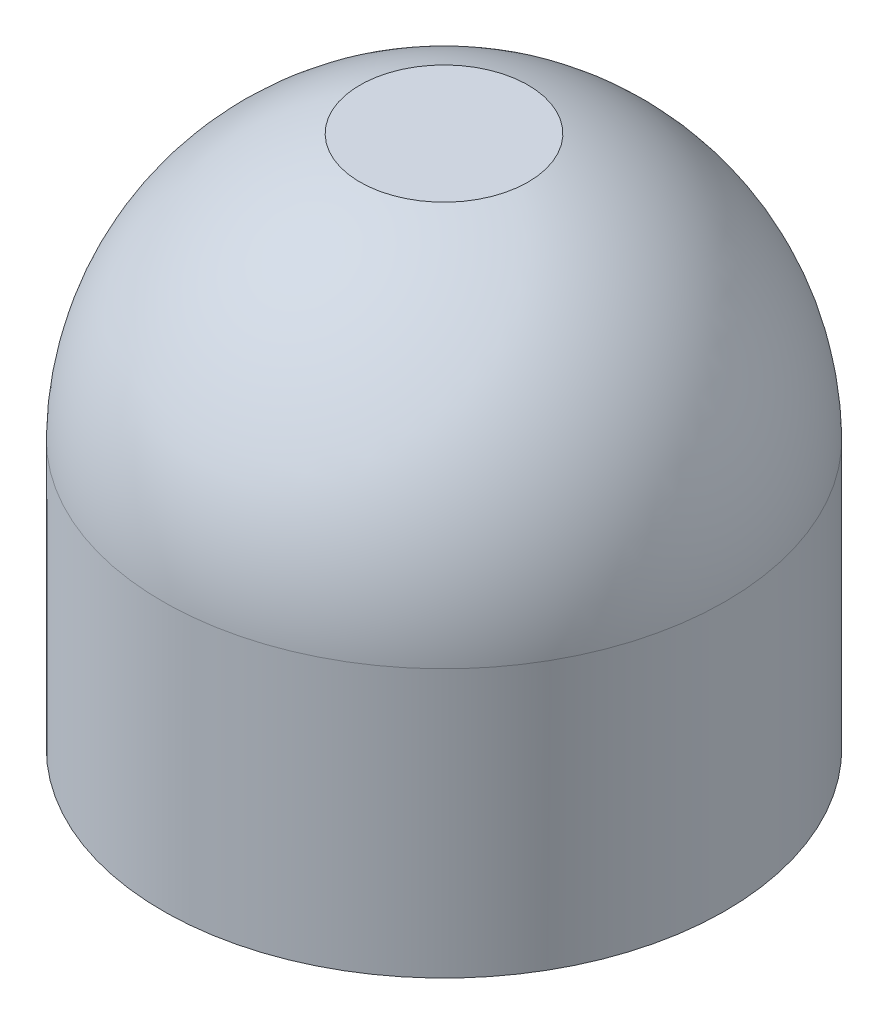
SolidWorks part; units mm, degrees
ref_plane "Front Plane" through (0, 0, 0) normal (0, 0, 1) x (1, 0, 0)
ref_plane "Top Plane" through (0, 0, 0) normal (0, 1, 0) x (1, 0, 0)
ref_plane "Right Plane" through (0, 0, 0) normal (1, 0, 0) x (0, 0, -1)
sketch "Sketch1" plane through (0, 0, 0) normal (0, 1, 0) x (1, 0, 0)
  circle A0 centre (0, 0) radius 5.25
  circle A1 centre (0, 0) radius 4.5
  point P5 (0, 0)
  dimension "D1" = 10.5
  dimension "D2" = 9
extrude "Boss-Extrude1" add sketch "Sketch1" along normal blind 5
sketch "Sketch2" plane through (0, 0, 0) normal (0, 1, 0) x (1, 0, 0)
  line L1 (1.3277, 3.7956) -> (1.3277, 5.7011)
  line L2 (1.3277, 5.7011) -> (-1.5, 5.7011)
  line L3 (-1.5, 5.7011) -> (-1.5, 3.7011)
  line L4 (-1.5, 3.7011) -> (1.3277, 3.7956)
extrude "Cut-Extrude1" cut sketch "Sketch2" along normal blind 5
sketch "Sketch4" plane through (0, 0, 0) normal (0, 0, 1) x (1, 0, 0)
  line L0 (5.25, 5) -> (0, 5)
  line L1 (0, 5) -> (0, 10.18)
  arc A0 (0, 10.18) -> (5.25, 5) centre (0, 4.9295) cw
  dimension "D2" = 5.18
  dimension "D3" = 5.25
revolve "Revolve1" add sketch "Sketch4" angle 360 about L1
ref_plane "Plane1" through (0, 5, 0) normal (0, -1, 0) x (-1, 0, 0)
sketch "Sketch5" plane through (0, 5, 0) normal (0, -1, 0) x (-1, 0, 0)
  line L2 (1.5, 3.4369) -> (1.5, 6)
  line L3 (1.5, 6) -> (-1.3277, 6)
  line L4 (-1.3277, 3.5071) -> (-1.3277, 6)
  arc A0 (-1.3277, 3.5071) -> (1.5, 3.4369) centre (0, 0) ccw
extrude "Cut-Extrude2" cut sketch "Sketch5" against normal blind 2
ref_plane "Plane2" through (0, 10.29, 0) normal (0, -1, 0) x (-1, 0, 0)
sketch "Sketch6" plane through (0, 10.29, 0) normal (0, -1, 0) x (-1, 0, 0)
  circle A0 centre (0, 0) radius 2
  point P4 (0, 0)
extrude "Cut-Extrude4" cut sketch "Sketch6" along normal blind 0.35
ref_plane "Plane3" through (1.3277, 0, 0) normal (-1, 0, 0) x (0, 0, 1)
sketch "Friction Bump" plane through (1.3277, 0, 0) normal (-1, 0, 0) x (0, 0, 1)
  line L0 (-4.2997, 5) -> (-4.2997, 0) construction
  line L1 (-4.2997, 2.0262) -> (-4.2997, 1.4262)
  line L2 (-4.2997, 2.0262) -> (-4.0997, 1.7943)
  line L3 (-4.2997, 1.4262) -> (-4.0997, 1.6585)
  line L4 (-4.0997, 1.6585) -> (-4.0997, 1.7943)
  point P6 (-4.2997, 1.7262)
  point P7 (-4.0997, 1.7264)
  dimension "D2" = 0.1358
  dimension "D1" = 0.6
  dimension "D3" = 0.2
  dimension "D4" = 0.0002
ref_plane "Plane4" through (0, 1.5, 0) normal (0, -1, 0) x (-1, 0, 0)
sketch "Sketch9" plane through (0, 1.5, 0) normal (0, -1, 0) x (-1, 0, 0)
  arc A1 (1.5, 4.2426) -> (-1.3277, 4.2997) centre (0, 0) cw
sweep "Sweep1" add profiles "Friction Bump" path "Sketch9"
